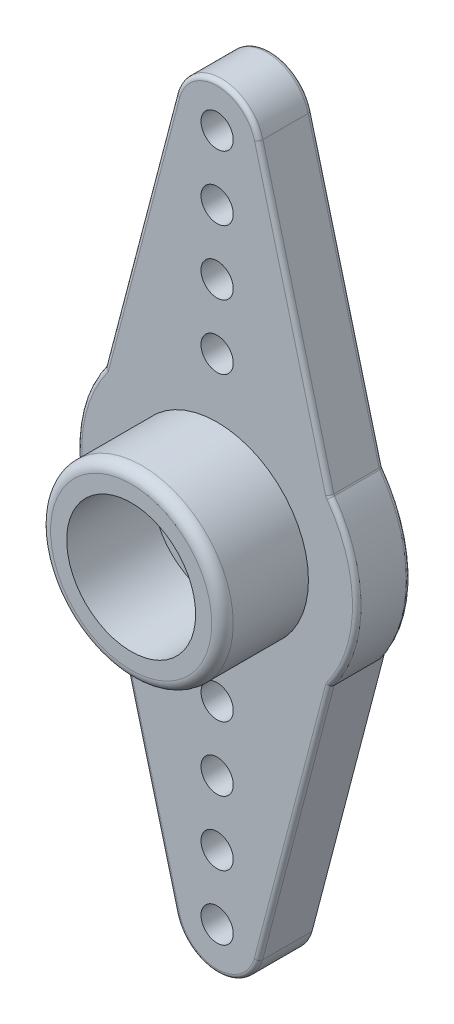
SolidWorks part; units mm, degrees
ref_plane "Front Plane" through (0, 0, 0) normal (0, 0, 1) x (1, 0, 0)
ref_plane "Top Plane" through (0, 0, 0) normal (0, 1, 0) x (1, 0, 0)
ref_plane "Right Plane" through (0, 0, 0) normal (1, 0, 0) x (0, 0, -1)
sketch "Sketch1" plane through (0, 0, 0) normal (0, 0, 1) x (1, 0, 0)
  line L0 (0, 18) -> (0, -18) construction
  line L4 (-6.25, 0) -> (6.25, 0) construction
  line L5 (1.935, 16.5058) -> (5.2471, 3.8365)
  line L6 (-1.935, 16.5058) -> (-5.2471, 3.8365)
  line L9 (1.9193, -16.5625) -> (5.2467, -3.8369)
  line L10 (-1.9193, -16.5625) -> (-5.2467, -3.8369)
  arc A0 (1.935, 16.5058) -> (-1.935, 16.5058) centre (0, 16) ccw
  arc A2 (-1.9193, -16.5625) -> (1.9193, -16.5625) centre (0, -16) ccw
  arc A3 (5.2467, -3.8369) -> (5.2471, 3.8365) centre (0, 0) ccw
  arc A4 (-5.2471, 3.8365) -> (-5.2467, -3.8369) centre (0, 0) ccw
  circle A18 centre (0, 7) radius 0.75
  circle A19 centre (0, 10) radius 0.75
  circle A20 centre (0, 13) radius 0.75
  circle A21 centre (0, 16) radius 0.75
  circle A22 centre (0, 0) radius 1.5
  circle A27 centre (0, -16) radius 0.75
  circle A28 centre (0, -13) radius 0.75
  circle A29 centre (0, -10) radius 0.75
  circle A30 centre (0, -7) radius 0.75
  arc A35 (16.5625, -1.9193) -> (16.5625, 1.9193) centre (16, 0) ccw [skipped]
  circle A36 centre (16, 0) radius 0.75 [skipped]
  circle A37 centre (13, 0) radius 0.75 [skipped]
  circle A38 centre (10, 0) radius 0.75 [skipped]
  arc A39 (-16.5625, 1.9193) -> (-16.5625, -1.9193) centre (-16, 0) ccw [skipped]
  circle A40 centre (-16, 0) radius 0.75 [skipped]
  circle A41 centre (-13, 0) radius 0.75 [skipped]
  circle A42 centre (-10, 0) radius 0.75 [skipped]
  circle A43 centre (-7, 0) radius 0.75 [skipped]
  circle A46 centre (7, 0) radius 0.75 [skipped]
  point P18 (0, 0)
  point P38 (0, 0)
  point P47 (0, 0)
  point P89 (0, 0)
  dimension "D2" = 12.5
  dimension "D4" = 13
  dimension "D9" = 7
  dimension "D10" = 1.5
  dimension "D11" = 10
  dimension "D12" = 13
  dimension "D13" = 16
  dimension "D14" = 3
  dimension "D3" = 4
  dimension "D15" = 4
extrude "Boss-Extrude1" add sketch "Sketch1" along normal blind 2.5
sketch "Sketch2" plane through (0, 0, 2.5) normal (0, 0, 1) x (1, 0, 0)
  circle A0 centre (0, 0) radius 4.25
  circle A1 centre (0, 0) radius 3
  dimension "D1" = 8.5
  dimension "D2" = 6
extrude "Boss-Extrude2" add sketch "Sketch2" along normal blind 4
sketch "Sketch3" plane through (0, 0, 0) normal (0, 0, -1) x (-1, 0, 0)
  circle A0 centre (0, 0) radius 4.5
  dimension "D1" = 9
extrude "Cut-Extrude1" cut sketch "Sketch3" against normal blind 0.8
sketch "Sketch4" plane through (0, 0, 0.8) normal (0, 0, -1) x (-1, 0, 0)
  circle A0 centre (0, 0) radius 3.5
  circle A1 centre (0, 0) radius 3.7
  dimension "D1" = 7
  dimension "D2" = 0.2
extrude "Boss-Extrude3" add sketch "Sketch4" along normal blind 1
fillet "Fillet2" radius 0.5 1 edges at (4.25, 0, 6.5)
fillet "Fillet3" radius 0.2 13 edges at (3.583, -10.1997, 2.5) (0, -18, 2.5) (-3.583, -10.1997, 2.5) (-3.591, 10.1712, 2.5) (0, 18, 2.5) (-3.591, 10.1712, 0) (0, 18, 0) (3.591, 10.1712, 2.5) (3.591, 10.1712, 0) (6.5, -0.0003, 2.5) (6.5, -0.0003, 0) (5.2471, 3.8365, 1.25) (-6.5, -0.0003, 2.5)
